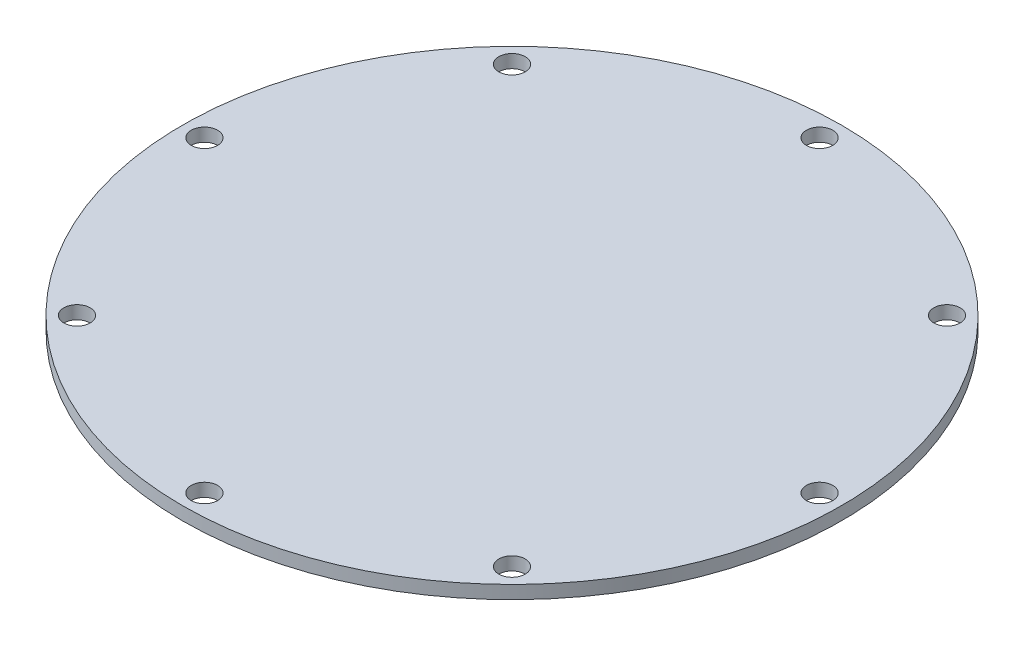
SolidWorks part; units mm, degrees
ref_plane "Спереди" through (0, 0, 0) normal (0, 0, 1) x (1, 0, 0)
ref_plane "Сверху" through (0, 0, 0) normal (0, 1, 0) x (1, 0, 0)
ref_plane "Справа" through (0, 0, 0) normal (1, 0, 0) x (0, 0, -1)
sketch "Эскиз1" plane through (0, 0, 0) normal (0, 1, 0) x (1, 0, 0)
  circle A0 centre (0, 0) radius 75
  point P3 (0, 0)
extrude "Бобышка-Вытянуть1" add sketch "Эскиз1" along normal blind 3 contours A0
sketch "Эскиз2" plane through (0, 3, 0) normal (0, 1, 0) x (1, 0, 0)
  line L0 (0, -75) -> (0, -70) construction
  line L1 (-75, 0) -> (75, 0) construction
  line L2 (0, 75) -> (0, -75) construction
  line L3 (0, 0) -> (-53.033, 53.033) construction
  line L4 (0, 0) -> (53.033, -53.033) construction
  line L5 (0, 0) -> (53.033, 53.033) construction
  line L6 (0, 0) -> (-53.033, -53.033) construction
  circle A0 centre (0, 0) radius 75 construction
  circle A1 centre (-70, 0) radius 3
  circle A2 centre (70, 0) radius 3
  circle A3 centre (0, -70) radius 3
  circle A4 centre (0, 70) radius 3
  circle A5 centre (-49.4975, -49.4975) radius 3
  circle A6 centre (-49.4975, 49.4975) radius 3
  circle A7 centre (49.4975, -49.4975) radius 3
  circle A8 centre (49.4975, 49.4975) radius 3
  point P23 (0, 0)
  dimension "D2" = 5
  dimension "D3" = 5
  dimension "D1" = 5
extrude "Вырез-Вытянуть1" cut sketch "Эскиз2" against normal blind 3
